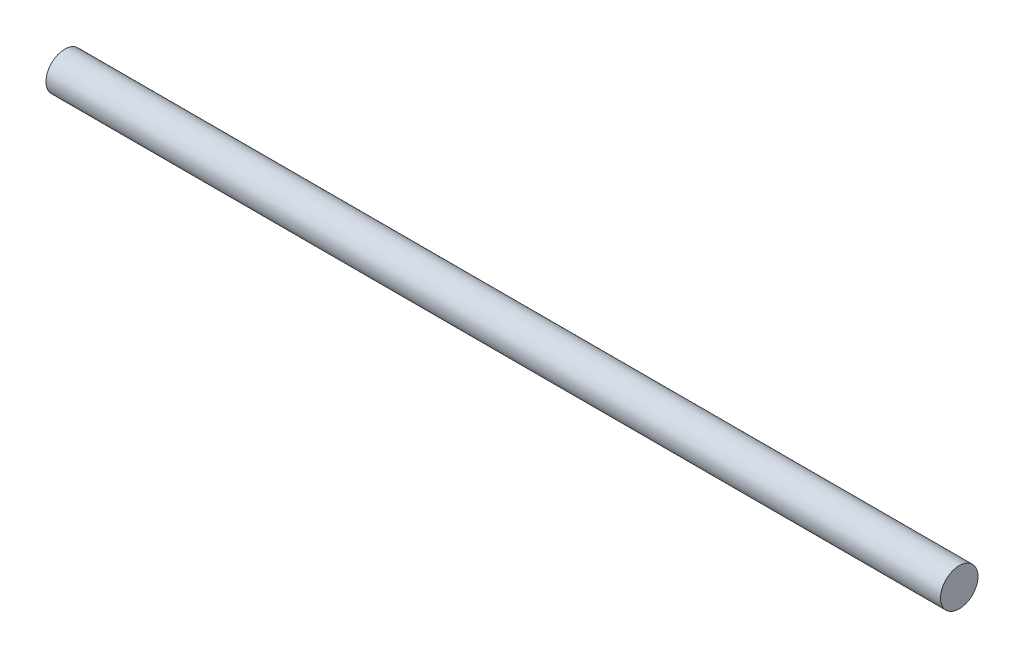
SolidWorks part; units mm, degrees
ref_plane "Alzado" through (0, 0, 0) normal (0, 0, 1) x (1, 0, 0)
ref_plane "Planta" through (0, 0, 0) normal (0, 1, 0) x (1, 0, 0)
ref_plane "Vista lateral" through (0, 0, 0) normal (1, 0, 0) x (0, 0, -1)
sketch "Croquis1" plane through (0, 0, 0) normal (1, 0, 0) x (0, 0, -1)
  circle A0 centre (0, 0) radius 6.5
  dimension "D1" = 13
extrude "Saliente-Extruir1" add sketch "Croquis1" along normal blind 310
